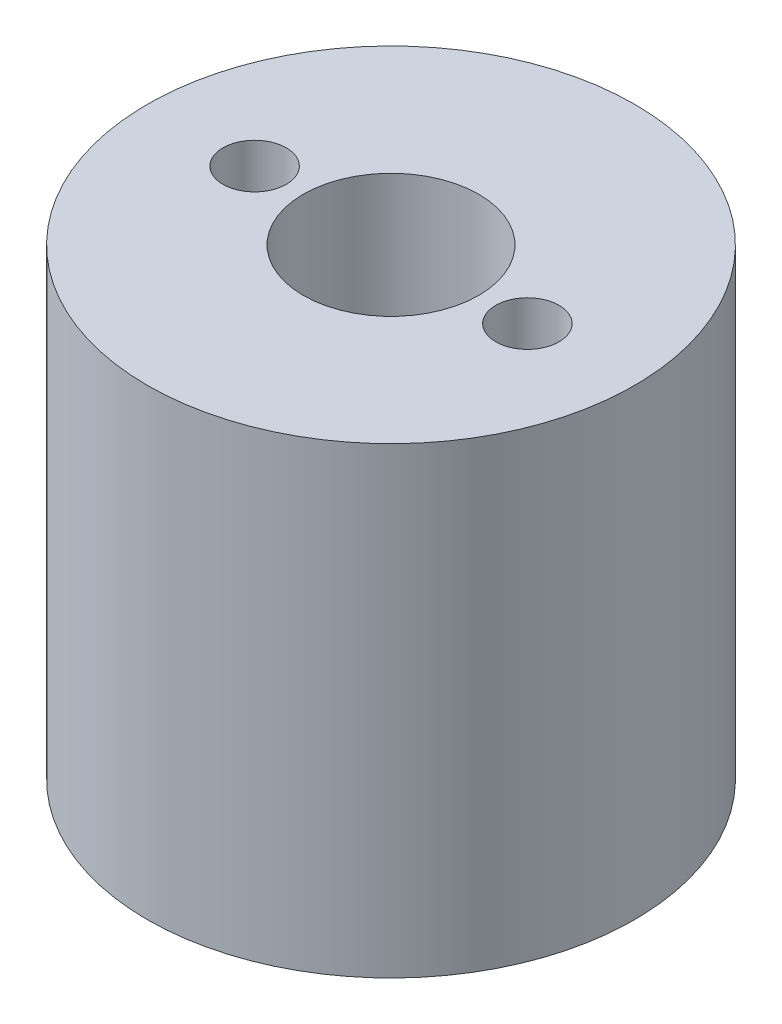
SolidWorks part; units mm, degrees
ref_plane "正面" through (0, 0, 0) normal (0, 0, 1) x (1, 0, 0)
ref_plane "平面" through (0, 0, 0) normal (0, 1, 0) x (1, 0, 0)
ref_plane "右側面" through (0, 0, 0) normal (1, 0, 0) x (0, 0, -1)
sketch "ｽｹｯﾁ1" plane through (0, 0, 0) normal (0, 1, 0) x (1, 0, 0)
  circle A0 centre (0, 0) radius 10
  circle A1 centre (0, 0) radius 2.1
  dimension "D1" = 4.2
  dimension "D2" = 20
extrude "ﾎﾞｽ - 押し出し1" add sketch "ｽｹｯﾁ1" along normal blind 5
sketch "ｽｹｯﾁ2" plane through (0, 5, 0) normal (0, 1, 0) x (1, 0, 0)
  circle A0 centre (0, 0) radius 3.6
  circle A1 centre (0, 0) radius 10
  circle A2 centre (0, 0) radius 10
  dimension "D2" = 7.2
  dimension "D1" = 0
extrude "ﾎﾞｽ - 押し出し2" add sketch "ｽｹｯﾁ2" along normal blind 14
sketch "ｽｹｯﾁ3" plane through (0, 19, 0) normal (0, 1, 0) x (1, 0, 0)
  line L0 (-5.6, 0) -> (5.6, 0) construction
  line L1 (-1.6, 0) -> (-1.6, -4.1221) construction
  line L2 (1.6, 0) -> (1.6, -4.1221) construction
  line L3 (1.6, -4.1221) -> (-1.6, -4.1221) construction
  circle A0 centre (5.6, 0) radius 4 construction
  circle A1 centre (-5.6, 0) radius 4 construction
  circle A2 centre (-5.6, 0) radius 1.3
  circle A3 centre (5.6, 0) radius 1.3
  dimension "D1" = 8
  dimension "D3" = 2.6
  dimension "D2" = 3.2
extrude "ｶｯﾄ - 押し出し1" cut sketch "ｽｹｯﾁ3" against normal through all
